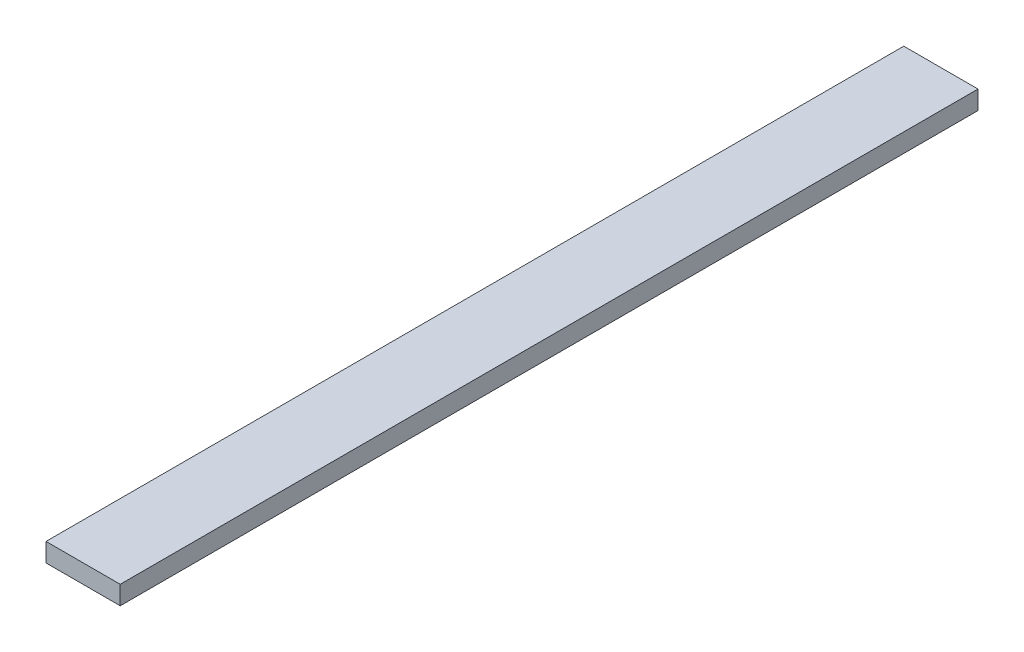
SolidWorks part; units mm, degrees
ref_plane "Front Plane" through (0, 0, 0) normal (0, 0, 1) x (1, 0, 0)
ref_plane "Top Plane" through (0, 0, 0) normal (0, 1, 0) x (1, 0, 0)
ref_plane "Right Plane" through (0, 0, 0) normal (1, 0, 0) x (0, 0, -1)
sketch "Sketch1" plane through (0, 0, 0) normal (0, 1, 0) x (1, 0, 0)
  line L1 (234.8905, 260.0514) -> (260.1786, 260.0514)
  line L2 (234.8905, 260.0514) -> (234.8905, -32.2184)
  line L3 (234.8905, -32.2184) -> (260.1786, -32.2184)
  line L4 (260.1786, 260.0514) -> (260.1786, -32.2184)
extrude "Boss-Extrude1" add sketch "Sketch1" along normal blind 6.3596 contours L2 L1 L4 L3
